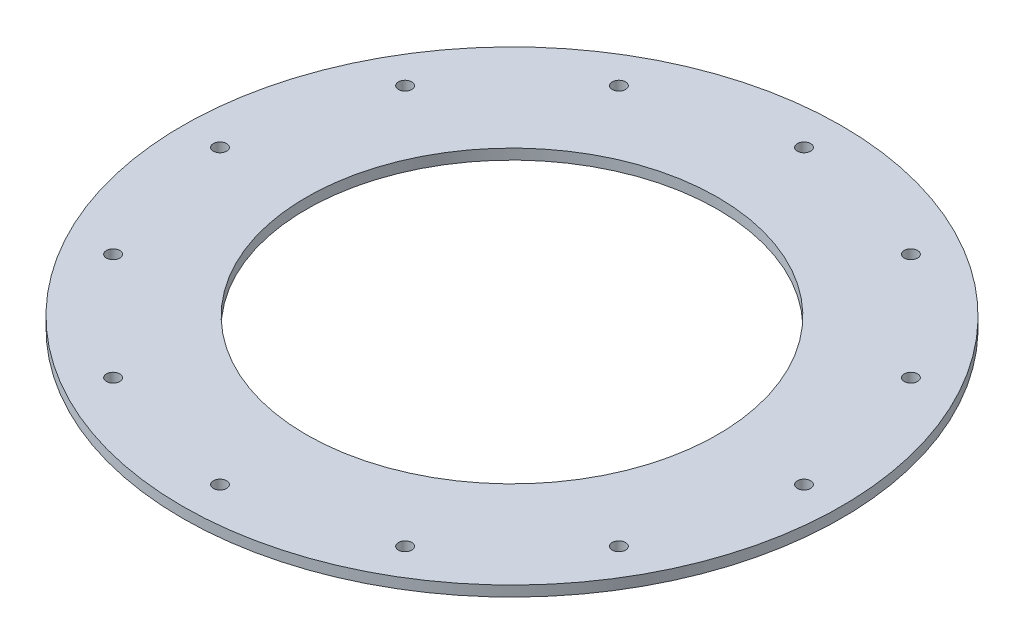
SolidWorks part; units mm, degrees
material "1060 Alloy"
ref_plane "Ebene vorne" through (0, 0, 0) normal (0, 0, 1) x (1, 0, 0)
ref_plane "Ebene oben" through (0, 0, 0) normal (0, 1, 0) x (1, 0, 0)
ref_plane "Ebene rechts" through (0, 0, 0) normal (1, 0, 0) x (0, 0, -1)
sketch "Sketch1" plane through (0, 0, 0) normal (0, 1, 0) x (1, 0, 0)
  circle A0 centre (0, 0) radius 49.3
  circle A1 centre (0, 0) radius 79
  dimension "D1" = 158
  dimension "D2" = 98.6
extrude "Boss-Extrude1" add sketch "Sketch1" along normal blind 2.5
sketch "Sketch2" plane through (0, 2.5, 0) normal (0, 1, 0) x (1, 0, 0)
  circle A0 centre (0, 70) radius 1.6
  circle A1 centre (35, 60.6218) radius 1.6
  circle A2 centre (60.6218, 35) radius 1.6
  circle A3 centre (70, 0) radius 1.6
  circle A4 centre (60.6218, -35) radius 1.6
  circle A5 centre (35, -60.6218) radius 1.6
  circle A6 centre (0, -70) radius 1.6
  circle A7 centre (-35, -60.6218) radius 1.6
  circle A8 centre (-60.6218, -35) radius 1.6
  circle A9 centre (-70, 0) radius 1.6
  circle A10 centre (-60.6218, 35) radius 1.6
  circle A11 centre (-35, 60.6218) radius 1.6
  point P28 (0, 0)
  dimension "D1" = 3.2
  dimension "D2" = 70
  dimension "D3" = 12
extrude "Cut-Extrude1" cut sketch "Sketch2" against normal through all
